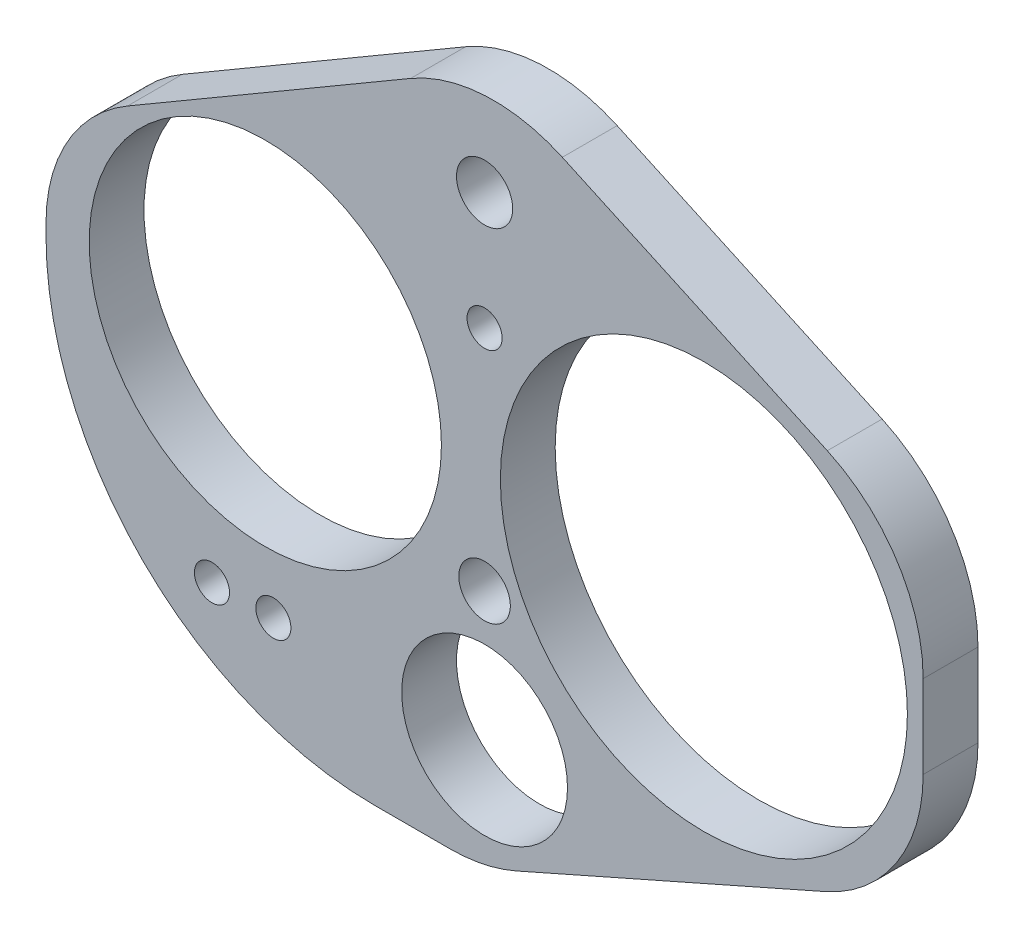
SolidWorks part; units mm, degrees
ref_plane "Front Plane" through (0, 0, 0) normal (0, 0, 1) x (1, 0, 0)
ref_plane "Top Plane" through (0, 0, 0) normal (0, 1, 0) x (1, 0, 0)
ref_plane "Right Plane" through (0, 0, 0) normal (1, 0, 0) x (0, 0, -1)
sketch "Sketch1" plane through (0, 0, 0) normal (0, 0, 1) x (1, 0, 0)
  line L0 (0, 0) -> (40, 0) construction
  line L1 (0.7371, -21.3168) -> (-4.8629, -21.3168)
  line L2 (-20, -31.5) -> (20, -31.5)
  line L3 (-20, -31.5) -> (-20, 8.1266)
  line L5 (60, -13.815) -> (60, 13.1418)
  line L6 (-20, -31.5) -> (60, 31.5) construction
  line L7 (-20, 31.5) -> (60, -31.5) construction
  line L8 (-20, 8.1266) -> (20, 31.5)
  line L9 (20, 31.5) -> (60, 13.1418)
  line L10 (60, -13.815) -> (20, -31.5)
  circle A0 centre (0, 0) radius 16.0625
  circle A1 centre (40, 0) radius 18.5625
  circle A2 centre (20, 11.209) radius 1.6
  circle A3 centre (20, -9.5571) radius 2.35
  circle A4 centre (20, 21.9186) radius 2.5625
  circle A5 centre (20, -21.3168) radius 7.5625
  circle A7 centre (0.7371, -21.3168) radius 1.6
  circle A8 centre (-4.8629, -21.3168) radius 1.6
  point P5 (20, 0)
  dimension "D1" = 32.125
  dimension "D2" = 37.125
  dimension "D6" = 3.2
  dimension "D7" = 4.7
  dimension "D8" = 5.125
  dimension "D9" = 15.125
  dimension "D12" = 3.2
  dimension "D13" = 3.2
  dimension "D3" = 40
  dimension "D4" = 80
  dimension "D5" = 63
  dimension "D11" = 5.6
extrude "Boss-Extrude1" add sketch "Sketch1" along normal blind 5
fillet "Fillet1" radius 15 5 edges at (60, -13.815, 2.5) (60, 13.1418, 2.5) (20, 31.5, 2.5) (-20, 8.1266, 2.5) (20, -31.5, 2.5)
fillet "Fillet2" radius 30 1 edges at (-20, -31.5, 2.5)
equation "\"RingPinShaft\"= 5"
equation "\"CenterBearingOut\"=32.125"
equation "\"RingPostIn\"=5.125"
equation "\"CamBearingOut\"=15.125"
equation "\"DiskOutputShaft\"=10"
equation "\"CenterShaft\"=25"
equation "\"Eccentricity\"=2"
equation "\"CycCamShaft\"=10"
equation "\"D1@Sketch1\"=\"CenterBearingOut\""
equation "\"OutputBearingOut\"=37.125"
equation "\"D2@Sketch1\"=\"OutputBearingOut\""
equation "\"D9@Sketch1\"=\"CamBearingOut\""
equation "\"D8@Sketch1\"=\"RingPostIn\""
